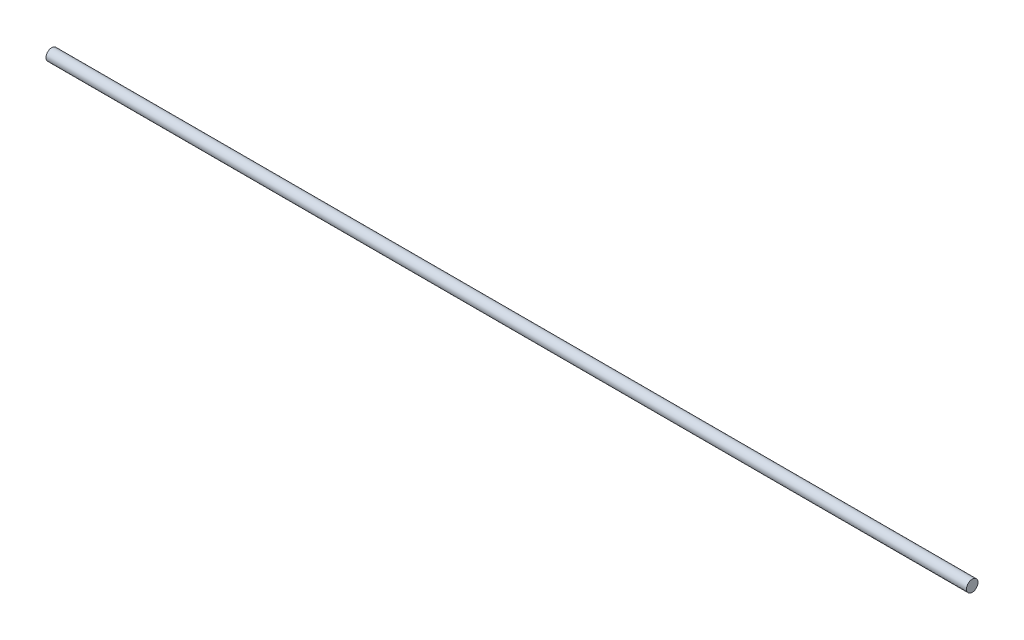
SolidWorks part; units mm, degrees
ref_plane "Front Plane" through (0, 0, 0) normal (0, 0, 1) x (1, 0, 0)
ref_plane "Top Plane" through (0, 0, 0) normal (0, 1, 0) x (1, 0, 0)
ref_plane "Right Plane" through (0, 0, 0) normal (1, 0, 0) x (0, 0, -1)
other "Bounding Box"
ref_plane "Default Plane" through (-400, -2.9884, -6.4086) normal (0, 0.9397, 0.342) x (1, 0, 0)
sketch "Sketch1" plane through (0, 0, 0) normal (1, 0, 0) x (0, 0, -1)
  circle A0 centre (0, 0) radius 5
  dimension "D1" = 10
extrude "Boss-Extrude1" add sketch "Sketch1" along normal mid plane 800
